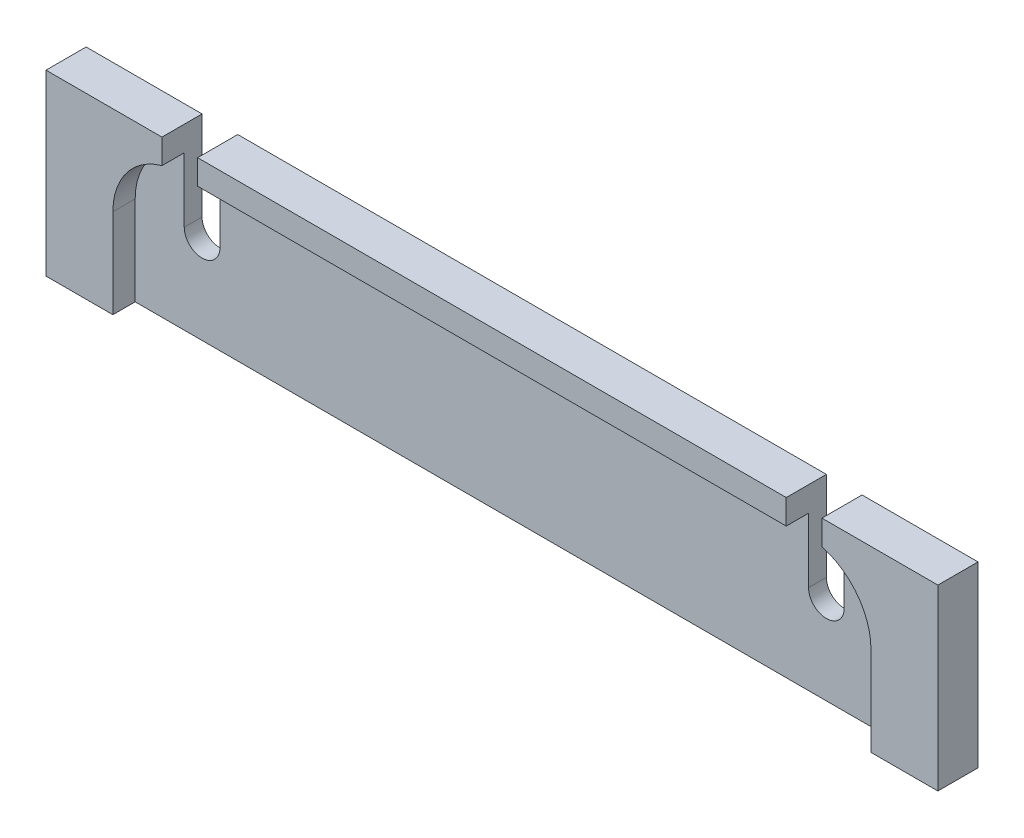
SolidWorks part; units mm, degrees
ref_plane "정면" through (0, 0, 0) normal (0, 0, 1) x (1, 0, 0)
ref_plane "윗면" through (0, 0, 0) normal (0, 1, 0) x (1, 0, 0)
ref_plane "우측면" through (0, 0, 0) normal (1, 0, 0) x (0, 0, -1)
sketch "스케치1" plane through (0, 0, 0) normal (0, 0, 1) x (1, 0, 0)
  line L0 (0, 0) -> (0, 40) construction
  line L1 (100, 0) -> (-100, 0)
  line L2 (-100, 0) -> (-100, 40)
  line L3 (-100, 40) -> (-74, 40)
  line L4 (-74, 20) -> (-74, 40)
  line L5 (-66, 20) -> (-66, 40)
  line L6 (-66, 40) -> (66, 40)
  line L7 (66, 20) -> (66, 40)
  line L8 (74, 20) -> (74, 40)
  line L9 (100, 40) -> (74, 40)
  line L10 (100, 0) -> (100, 40)
  arc A1 (-74, 20) -> (-66, 20) centre (-70, 20) ccw
  arc A2 (74, 20) -> (66, 20) centre (70, 20) cw
  point P2 (0, 30)
  dimension "D4" = 4
  dimension "D1" = 200
  dimension "D2" = 20
  dimension "D3" = 20
  dimension "D5" = 70
extrude "보스-돌출1" add sketch "스케치1" along normal blind 4
sketch "스케치2" plane through (0, 0, 4) normal (0, 0, 1) x (1, 0, 0)
  line L0 (-74, 34.4568) -> (-74, 40)
  line L2 (-74, 40) -> (-100, 40)
  line L3 (-100, 40) -> (-100, 0)
  line L4 (-100, 0) -> (-85, 0)
  line L5 (-100, 0) -> (100, 0) construction
  line L6 (-85, 0) -> (-85, 20)
  line L7 (-66, 34.4568) -> (66, 34.4568)
  line L8 (-66, 40) -> (-66, 34.4568)
  line L10 (-74, 34.4568) -> (-66, 34.4568) construction
  line L11 (66, 34.4568) -> (66, 40)
  line L12 (66, 20) -> (66, 40) construction
  line L13 (66, 40) -> (-66, 40)
  line L14 (74, 40) -> (74, 34.4568)
  line L16 (74, 40) -> (100, 40)
  line L17 (100, 40) -> (100, 0)
  line L18 (100, 0) -> (85, 0)
  line L19 (85, 0) -> (85, 20)
  line L21 (74, 40) -> (74, 20) construction
  line L22 (66, 34.4568) -> (74, 34.4568) construction
  arc A0 (-74, 34.4568) -> (-85, 20) centre (-70, 20) ccw
  arc A1 (85, 20) -> (74, 34.4568) centre (70, 20) ccw
  dimension "D1" = 15
  dimension "D2" = 15
  dimension "D3" = 15
extrude "보스-돌출2" add sketch "스케치2" along normal blind 5
